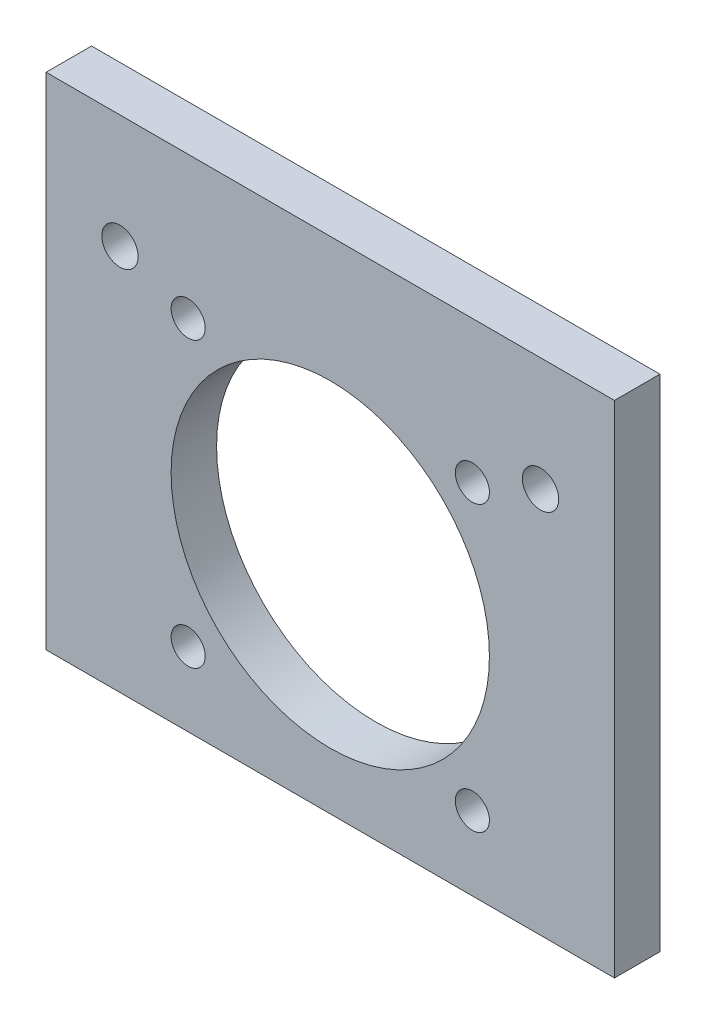
SolidWorks part; units mm, degrees
ref_plane "Płaszczyzna przednia" through (0, 0, 0) normal (0, 0, 1) x (1, 0, 0)
ref_plane "Płaszczyzna górna" through (0, 0, 0) normal (0, 1, 0) x (1, 0, 0)
ref_plane "Płaszczyzna prawa" through (0, 0, 0) normal (1, 0, 0) x (0, 0, -1)
sketch "Sketch1" plane through (0, 0, 0) normal (0, 0, 1) x (1, 0, 0)
  line L1 (0, 0) -> (50, 0)
  line L2 (0, 0) -> (0, 44)
  line L3 (0, 44) -> (50, 44)
  line L4 (50, 0) -> (50, 44)
  dimension "D1" = 50
  dimension "D2" = 44
extrude "Boss-Extrude1" add sketch "Sketch1" along normal blind 4
hole_wizard "Ø3.0mm Dowel Hole1" positions "Sketch2" profile "Sketch3" hole size "Ø3.0" standard "ANSI Metric" end condition through all
sketch "Sketch2" plane through (0, 0, 4) normal (0, 0, 1) x (1, 0, 0)
  line L0 (0, 44) -> (0, 0) construction
  line L1 (50, 44) -> (0, 44) construction
  point P0 (6.5, 34)
  point P2 (43.5, 34)
  point P5 (0, 0)
  dimension "D1" = 37
  dimension "D2" = 6.5
  dimension "D3" = 10
sketch "Sketch3" plane through (6.5, 34, 4) normal (1, 0, 0) x (0, -1, 0)
  line L0 (0, 0) -> (0, 4)
  line L1 (0, 4) -> (1.6, 4)
  line L2 (1.6, 4) -> (1.6, 0)
  line L5 (1.6, 0) -> (0, 0)
  line L11 (0, -6.35) -> (0, 107.95) construction
  dimension "Thru Hole Dia." = 3.2
  dimension "Thru Hole Depth" = 4
sketch "Sketch4" plane through (0, 0, 4) normal (0, 0, 1) x (1, 0, 0)
  line L0 (25, 0) -> (25, 44) construction
  line L1 (0, 0) -> (50, 0) construction
  line L2 (50, 44) -> (0, 44) construction
  circle A0 centre (25, 19) radius 14
  point P8 (0, 0)
  point P9 (25, 17.9496)
  dimension "D1" = 28
  dimension "D2" = 19
extrude "Cut-Extrude1" cut sketch "Sketch4" against normal blind 4
hole_wizard "Ø3.0mm Dowel Hole2" positions "Sketch5" profile "Sketch6" hole size "Ø3.0" standard "ANSI Metric" end condition through all
sketch "Sketch5" plane through (0, 0, 4) normal (0, 0, 1) x (1, 0, 0)
  line L1 (10, 34) -> (40, 34)
  line L2 (10, 34) -> (10, 4)
  line L3 (10, 4) -> (40, 4)
  line L4 (40, 34) -> (40, 4)
  line L5 (10, 34) -> (40, 4) construction
  line L6 (10, 4) -> (40, 34) construction
  line L7 (0, 0) -> (50, 0) construction
  line L8 (0, 44) -> (0, 0) construction
  point P0 (12.5, 31.5)
  point P119 (25, 19)
  point P135 (37.5, 31.5)
  point P136 (37.5, 6.5)
  point P137 (12.5, 6.5)
  dimension "D1" = 30
  dimension "D2" = 4
  dimension "D3" = 10
  dimension "D4" = 2.5
  dimension "D5" = 2.5
  dimension "D6" = 4
sketch "Sketch6" plane through (12.5, 31.5, 4) normal (1, 0, 0) x (0, -1, 0)
  line L0 (0, 0) -> (0, 4)
  line L1 (0, 4) -> (1.5, 4)
  line L2 (1.5, 4) -> (1.5, 0)
  line L5 (1.5, 0) -> (0, 0)
  line L11 (0, -6.35) -> (0, 107.95) construction
  dimension "Thru Hole Dia." = 3
  dimension "Thru Hole Depth" = 4
